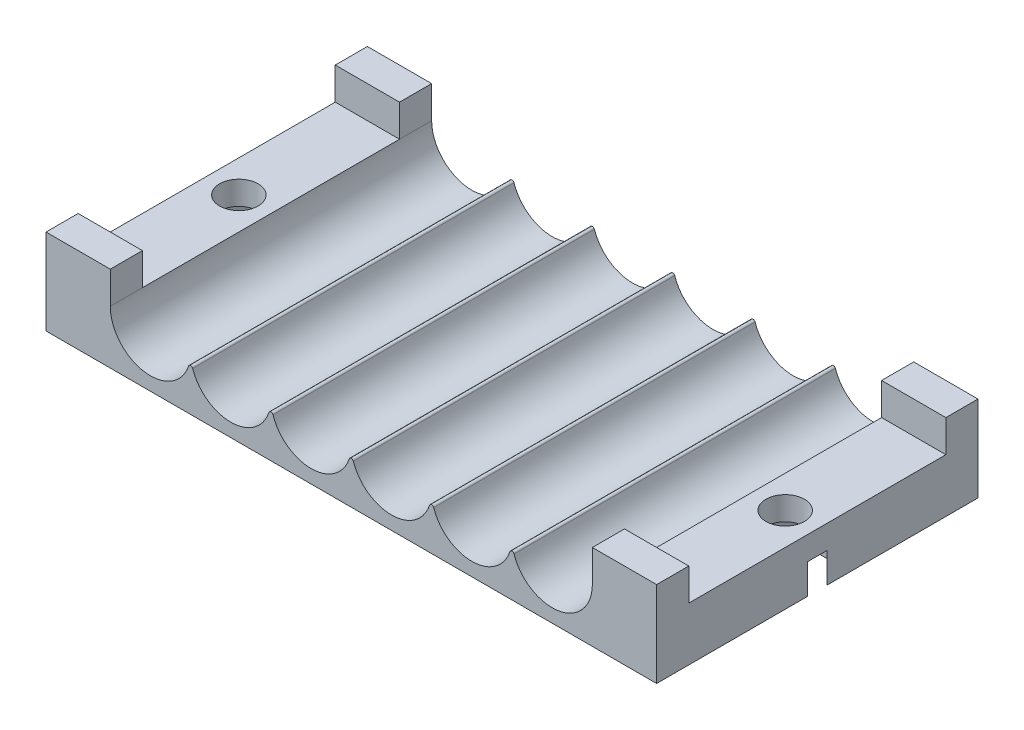
SolidWorks part; units mm, degrees
ref_plane "Plano frontal" through (0, 0, 0) normal (0, 0, 1) x (1, 0, 0)
ref_plane "Plano superior" through (0, 0, 0) normal (0, 1, 0) x (1, 0, 0)
ref_plane "Plano direito" through (0, 0, 0) normal (1, 0, 0) x (0, 0, -1)
sketch "Esboço1" plane through (0, 0, 0) normal (0, 0, 1) x (1, 0, 0)
  line L0 (-22.5, 5) -> (-22.5, 0) construction
  line L1 (-22.5, 0) -> (22.5, 0)
  line L2 (22.5, 0) -> (22.5, 5) construction
  line L3 (-22.5, 5) -> (22.5, 5) construction
  line L4 (-22.5, 5) -> (-28.5, 5)
  line L5 (-28.5, 5) -> (-28.5, 0)
  line L6 (-28.5, 0) -> (-22.5, 0)
  line L7 (0, -55) -> (0, 55) construction
  line L8 (28.5, 0) -> (22.5, 0)
  line L9 (28.5, 5) -> (28.5, 0)
  line L10 (22.5, 5) -> (28.5, 5)
  arc A0 (-22.5, 5) -> (-15, 5) centre (-18.75, 5) ccw
  arc A1 (-15, 5) -> (-7.5, 5) centre (-11.25, 5) ccw
  arc A2 (-7.5, 5) -> (0, 5) centre (-3.75, 5) ccw
  arc A3 (0, 5) -> (7.5, 5) centre (3.75, 5) ccw
  arc A4 (7.5, 5) -> (15, 5) centre (11.25, 5) ccw
  arc A5 (15, 5) -> (22.5, 5) centre (18.75, 5) ccw
  point P2 (0, 0)
  dimension "D1" = 7.5
  dimension "D3" = 5
  dimension "D4" = 6
  dimension "D2" = 6
extrude "Ressalto-extrusão1" add sketch "Esboço1" along normal mid plane 30
sketch "Esboço2" plane through (0, 5, 0) normal (0, 1, 0) x (1, 0, 0)
  line L0 (-22.5, 15) -> (-28.5, 15) construction
  line L1 (-28.5, -15) -> (-28.5, 15) construction
  line L2 (0, -2.75) -> (0, 2.75) construction
  circle A0 centre (-25.5, 0) radius 1.8
  circle A1 centre (25.5, 0) radius 1.8
  point P5 (-25.5, 15)
  point P8 (-28.5, 0)
  dimension "D1" = 3.6
extrude "Corte-extrusão1" cut sketch "Esboço2" against normal through all
sketch "Esboço3" plane through (0, 5, 0) normal (0, 1, 0) x (1, 0, 0)
  line L18 (-15, 15) -> (-22.5, 15) construction
  line L19 (-28.5, 15) -> (-22.5, 15)
  line L20 (-28.5, 15) -> (-28.5, 12)
  line L21 (-28.5, 12) -> (-22.5, 12)
  line L22 (-22.5, 15) -> (-22.5, 12)
  line L23 (0, -15) -> (0, 15) construction
  line L24 (-28.5, -15) -> (-22.5, -15)
  line L25 (-28.5, -15) -> (-28.5, -12)
  line L26 (-28.5, -12) -> (-22.5, -12)
  line L27 (-22.5, -15) -> (-22.5, -12)
  line L28 (22.5, -15) -> (22.5, -12)
  line L29 (28.5, -12) -> (22.5, -12)
  line L30 (28.5, -15) -> (28.5, -12)
  line L31 (28.5, -15) -> (22.5, -15)
  line L32 (22.5, 15) -> (22.5, 12)
  line L33 (28.5, 12) -> (22.5, 12)
  line L34 (28.5, 15) -> (28.5, 12)
  line L35 (28.5, 15) -> (22.5, 15)
  point P4 (-22.5, 15)
  point P7 (-18.75, 15)
  dimension "D1" = 3
fillet "Filete1" radius 0.2 5 edges at (15, 5, 0) (7.5, 5, 0) (0, 5, 0) (-7.5, 5, 0) (-15, 5, 0)
extrude "Ressalto-extrusão2" add sketch "Esboço3" along normal blind 3
sketch "Esboço4" plane through (0, 0, 0) normal (0, -1, 0) x (1, 0, 0)
  line L0 (-29.0218, 0) -> (-27.2609, -3.05)
  line L1 (-27.2609, -3.05) -> (-23.7391, -3.05)
  line L2 (-23.7391, -3.05) -> (-21.9782, 0)
  line L3 (-21.9782, 0) -> (-23.7391, 3.05)
  line L4 (-23.7391, 3.05) -> (-27.2609, 3.05)
  line L5 (-27.2609, 3.05) -> (-29.0218, 0)
  line L6 (0, -4.4) -> (0, 4.4) construction
  line L7 (27.2609, 3.05) -> (29.0218, 0)
  line L8 (23.7391, 3.05) -> (27.2609, 3.05)
  line L9 (21.9782, 0) -> (23.7391, 3.05)
  line L10 (23.7391, -3.05) -> (21.9782, 0)
  line L11 (27.2609, -3.05) -> (23.7391, -3.05)
  line L12 (29.0218, 0) -> (27.2609, -3.05)
  circle A0 centre (-25.5, 0) radius 3.5218 construction
  circle A1 centre (25.5, 0) radius 3.5218 construction
  dimension "D1" = 6.1
extrude "Corte-extrusão2" cut sketch "Esboço4" against normal blind 2.8
